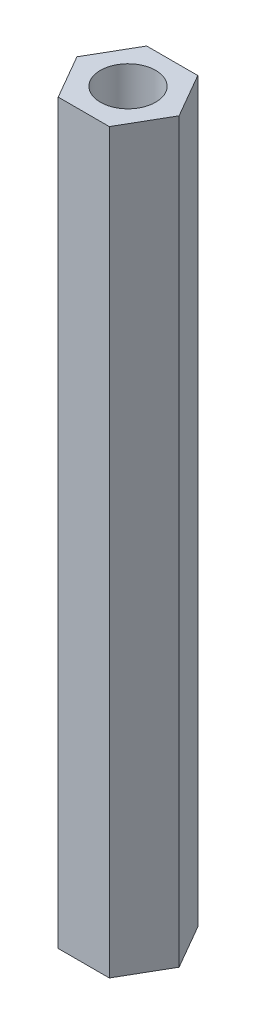
SolidWorks part; units mm, degrees
ref_plane "Front Plane" through (0, 0, 0) normal (0, 0, 1) x (1, 0, 0)
ref_plane "Top Plane" through (0, 0, 0) normal (0, 1, 0) x (1, 0, 0)
ref_plane "Right Plane" through (0, 0, 0) normal (1, 0, 0) x (0, 0, -1)
sketch "Sketch1" plane through (0, 0, 0) normal (0, 1, 0) x (1, 0, 0)
  line L1 (-1.3856, 2.4) -> (-2.7713, 0)
  line L2 (-2.7713, 0) -> (-1.3856, -2.4)
  line L3 (-1.3856, -2.4) -> (1.3856, -2.4)
  line L4 (1.3856, -2.4) -> (2.7713, 0)
  line L5 (2.7713, 0) -> (1.3856, 2.4)
  line L6 (1.3856, 2.4) -> (-1.3856, 2.4)
  circle A0 centre (0, 0) radius 1.5
  circle A1 centre (0, 0) radius 2.4 construction
  dimension "D1" = 3
  dimension "D2" = 4.8
extrude "Boss-Extrude1" add sketch "Sketch1" along normal blind 40
